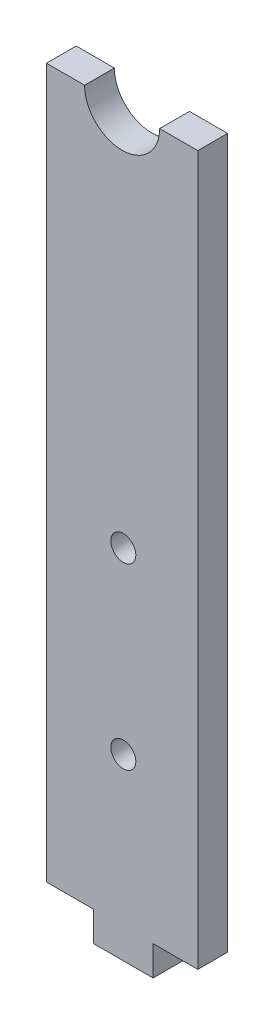
SolidWorks part; units mm, degrees
material "Plain Carbon Steel"
ref_plane "Front Plane" through (0, 0, 0) normal (0, 0, 1) x (1, 0, 0)
ref_plane "Top Plane" through (0, 0, 0) normal (0, 1, 0) x (1, 0, 0)
ref_plane "Right Plane" through (0, 0, 0) normal (1, 0, 0) x (0, 0, -1)
sketch "Sketch1" plane through (0, 0, 0) normal (0, 0, 1) x (1, 0, 0)
  line L1 (-37.6912, 13.9321) -> (-12.2912, 13.9321)
  line L2 (-37.6912, 13.9321) -> (-37.6912, -110.0679)
  line L3 (-37.6912, -110.0679) -> (-12.2912, -110.0679)
  line L4 (-12.2912, 13.9321) -> (-12.2912, -110.0679)
  dimension "D1" = 124
  dimension "D2" = 25.4
extrude "Boss-Extrude1" add sketch "Sketch1" along normal blind 5
sketch "Sketch2" plane through (0, 0, 5) normal (0, 0, 1) x (1, 0, 0)
  line L0 (-37.6912, -110.0679) -> (-12.2912, -110.0679) construction
  circle A0 centre (-24.7912, -50.0679) radius 2.1
  circle A1 centre (-24.7912, -80.0679) radius 2.1
  dimension "D1" = 4.2
  dimension "D2" = 30
  dimension "D4" = 30
extrude "Cut-Extrude1" cut sketch "Sketch2" against normal blind 35
sketch "Sketch3" plane through (0, 0, 0) normal (0, 0, -1) x (-1, 0, 0)
  line L0 (12.2912, -110.0679) -> (12.2912, 13.9321) construction
  line L1 (37.7691, 37.1735) -> (12.2912, 37.1735)
  line L2 (37.7691, 37.1735) -> (37.7691, 44.1735)
  line L3 (37.7691, 44.1735) -> (12.2912, 44.1735)
  line L4 (12.2912, 37.1735) -> (12.2912, 44.1735)
  line L5 (37.7691, 37.1735) -> (12.2912, 44.1735) construction
  line L6 (37.7691, 44.1735) -> (12.2912, 37.1735) construction
  point P0 (25.0302, 40.6735)
  dimension "D1" = 7
extrude "Cut-Extrude2" [suppressed] cut sketch "Sketch3" against normal blind 5
sketch "Sketch4" plane through (0, 0, 0) normal (0, 0, -1) x (-1, 0, 0)
  line L0 (37.6912, -110.0679) -> (12.2912, -110.0679) construction
  line L2 (19.7912, -110.0679) -> (19.7912, -115.0679)
  line L3 (19.7912, -115.0679) -> (29.7912, -115.0679)
  line L4 (29.7912, -110.0679) -> (29.7912, -115.0679)
  line L5 (24.9912, -110.0679) -> (29.7912, -115.0679) construction
  line L6 (19.7912, -115.0679) -> (24.9912, -110.0679) construction
  line L7 (19.7912, -110.0679) -> (29.7912, -110.0679)
  point P0 (24.9912, -110.0679)
  point P2 (24.7912, -110.0679)
  dimension "D1" = 10
  dimension "D2" = 5
extrude "Boss-Extrude2" [suppressed] add sketch "Sketch4" against normal blind 10
sketch "Sketch5" plane through (0, 0, 0) normal (0, 0, -1) x (-1, 0, 0)
  line L1 (12.2912, -110.0679) -> (19.7912, -110.0679)
  line L2 (12.2912, -110.0679) -> (12.2912, -105.0679)
  line L3 (12.2912, -105.0679) -> (19.7912, -105.0679)
  line L4 (19.7912, -110.0679) -> (19.7912, -105.0679)
  line L5 (37.6912, -110.0679) -> (29.7912, -110.0679)
  line L6 (37.6912, -110.0679) -> (37.6912, -105.0679)
  line L7 (37.6912, -105.0679) -> (29.7912, -105.0679)
  line L8 (29.7912, -110.0679) -> (29.7912, -105.0679)
  dimension "D1" = 5
  dimension "D2" = 10
  dimension "D3" = 7.5
extrude "Cut-Extrude3" cut sketch "Sketch5" against normal blind 10
sketch "Sketch7" plane through (0, 0, 0) normal (0, 0, -1) x (-1, 0, 0)
  line L0 (12.2912, 13.9321) -> (37.6912, 13.9321) construction
  line L1 (18.6912, 13.9321) -> (31.2912, 13.9321)
  arc A0 (31.2912, 13.9321) -> (18.6912, 13.9321) centre (24.9912, 13.9321) cw
  dimension "D1" = 6.3
extrude "Cut-Extrude4" cut sketch "Sketch7" against normal blind 10
